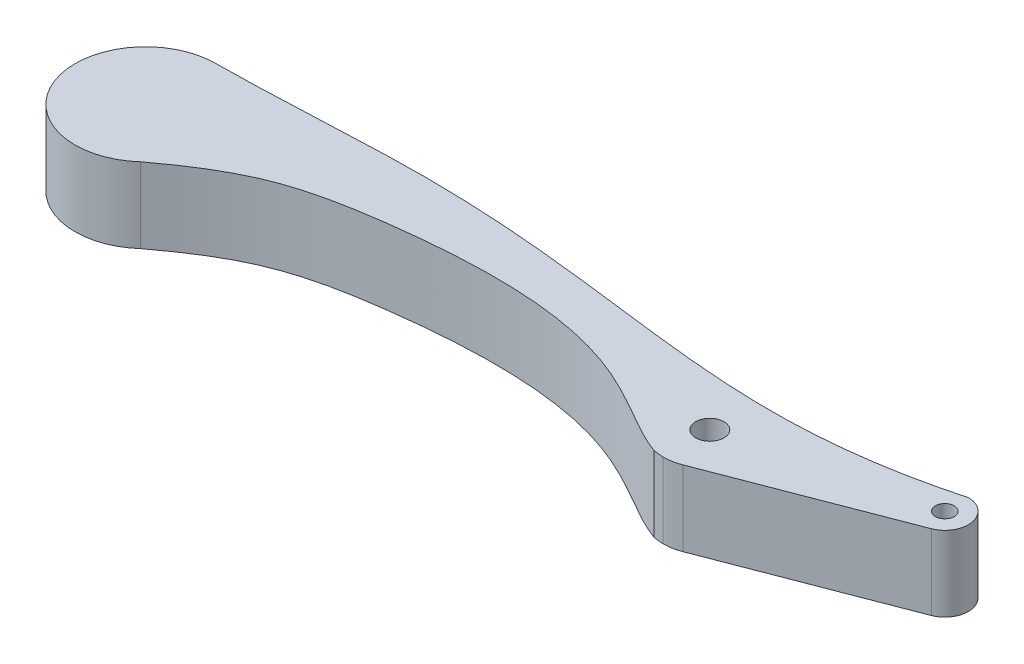
SolidWorks part; units mm, degrees
ref_plane "前视基准面" through (0, 0, 0) normal (0, 0, 1) x (1, 0, 0)
ref_plane "上视基准面" through (0, 0, 0) normal (0, 1, 0) x (1, 0, 0)
ref_plane "右视基准面" through (0, 0, 0) normal (1, 0, 0) x (0, 0, -1)
other "Configuration Table"
sketch "Sketch1" plane through (0, 0, 0) normal (0, 1, 0) x (1, 0, 0)
  line L0 (55, 0.0297) -> (60, 0.0297) construction
  line L1 (0, 7.5) -> (15, 6.8824)
  line L2 (79.3846, 7.4528) -> (80, 7.5297)
  line L3 (0, -7.5) -> (0.6313, -7.4734)
  line L4 (61.792, -4.6381) -> (80.896, 2.6958)
  line L5 (15, 0.0297) -> (4.0224, -6.3301) construction
  line L6 (15, 0.0297) -> (15, 8.0297) construction
  circle A0 centre (0, 0) radius 7.5
  circle A1 centre (60, 0.0297) radius 1.5
  circle A2 centre (60, 0.0297) radius 5
  circle A3 centre (80, 5.0297) radius 1
  circle A4 centre (80, 5.0297) radius 2.5
  spline S0 degree 3 poles (5.0373, -5.5566) (8.0216, -3.3229) (13.6358, 0.2367) (47.1128, 6.0862) (52.1284, -2.3765) (58.9707, -4.8632) knots 0.020667 0.020667 0.020667 0.020667 0.119806 0.217739 1 1 1 1
  spline S1 degree 3 poles (58.9707, -4.8632) (58.9781, -4.8632) (59.9926, -4.9703) (60, -4.9703) knots 0.714199 0.714199 0.714199 0.714199 0.714488 0.714488 0.714488 0.714488
  spline S2 degree 3 poles (0, 7.5) (6.5962, 7.5304) (41.0182, 10.2663) (57.4957, 1.4317) (80, 7.5297) knots 0 0 0 0 0.213971 1 1 1 1
  point P16 (15, 0.0297)
  dimension "D1" = 15
  dimension "D2" = 3
  dimension "D4" = 10
  dimension "D5" = 2
  dimension "D8" = 5
  dimension "D3" = 60
  dimension "D6" = 20
  dimension "D7" = 5
  dimension "D9" = 15
  dimension "D10" = 8
extrude "Boss-Extrude2" add sketch "Sketch1" along normal blind 8
sketch "Sketch2" plane through (0, 0, 0) normal (0, 1, 0) x (1, 0, 0)
  circle A0 centre (0, 0) radius 7.5
extrude "Boss-Extrude3" add sketch "Sketch2" along normal blind 8
